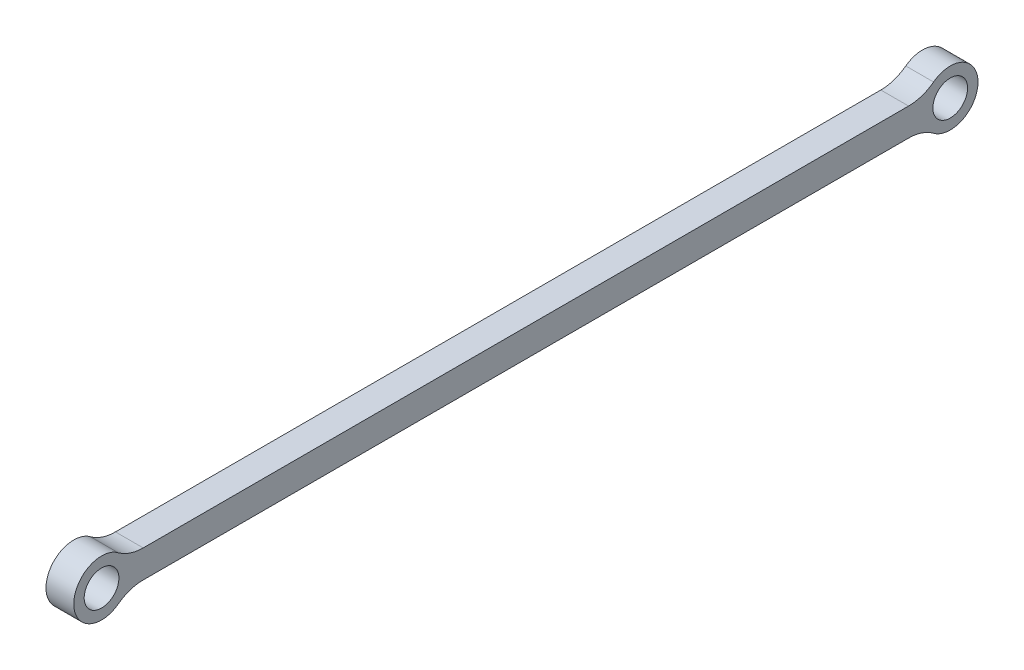
SolidWorks part; units mm, degrees
material "Thornel Mat VMA"
ref_plane "前视基准面" through (0, 0, 0) normal (0, 0, 1) x (1, 0, 0)
ref_plane "上视基准面" through (0, 0, 0) normal (0, 1, 0) x (1, 0, 0)
ref_plane "右视基准面" through (0, 0, 0) normal (1, 0, 0) x (0, 0, -1)
sketch "草图1" plane through (0, 0, 0) normal (1, 0, 0) x (0, 0, -1)
  line L0 (0, 0) -> (244.5, 0) construction
  line L1 (0, 8) -> (244.5, 8)
  line L2 (0, -8) -> (244.5, -8)
  arc A0 (0, 8) -> (0, -8) centre (0, 0) ccw
  arc A1 (244.5, -8) -> (244.5, 8) centre (244.5, 0) ccw
  circle A2 centre (244.5, 0) radius 5
  circle A3 centre (0, 0) radius 5
  point P3 (122.25, 0)
  dimension "D1" = 10
  dimension "D2" = 10
  dimension "D3" = 16
  dimension "D4" = 244.5
extrude "凸台-拉伸1" add sketch "草图1" along normal blind 8
sketch "草图2" plane through (8, 0, 0) normal (1, 0, 0) x (0, 0, -1)
  line L0 (0, 0) -> (244.5, 0) construction
  line L1 (0, -8) -> (244.5, -8) construction
  line L2 (244.5, 8) -> (0, 8) construction
  line L3 (237.5718, -4) -> (6.9282, -4)
  line L4 (237.5718, 4) -> (6.9282, 4)
  line L5 (0, -8) -> (244.5, -8)
  line L6 (244.5, 8) -> (0, 8)
  arc A0 (0, -8) -> (6.9282, -4) centre (0, 0) ccw
  arc A1 (0, 8) -> (0, -8) centre (0, 0) ccw construction
  arc A2 (244.5, 8) -> (237.5718, 4) centre (244.5, 0) ccw
  arc A3 (6.9282, 4) -> (0, 8) centre (0, 0) ccw
  arc A4 (237.5718, -4) -> (244.5, -8) centre (244.5, 0) ccw
  dimension "D1" = 8
extrude "切除-拉伸1" cut sketch "草图2" against normal through all
fillet "圆角1" radius 12 4 edges at (4, -4, -237.5718) (4, 4, -6.9282) (4, -4, -6.9282) (4, 4, -237.5718)
sketch "草图4" plane through (8, 0, 0) normal (1, 0, 0) x (0, 0, -1)
  line L0 (0, 0) -> (244.5, 0) construction
  line L1 (122.25, 0) -> (122.25, 19.2035) construction
  line L2 (12, 4) -> (232.5, 4) construction
  line L6 (121.75, 2.2) -> (109.75, 2.2)
  line L9 (121.75, 2.2) -> (121.75, -2.2)
  line L12 (121.75, -2.2) -> (109.75, -2.2)
  line L15 (109.75, 2.2) -> (109.75, -2.2)
  line L18 (121.75, 2.2) -> (109.75, -2.2) construction
  line L21 (214.75, -2.2) -> (200.75, 2.2) construction
  line L24 (121.75, -2.2) -> (109.75, 2.2) construction
  line L27 (108.75, 2.2) -> (96.75, 2.2)
  line L30 (96.75, 2.2) -> (96.75, -2.2)
  line L33 (108.75, 2.2) -> (108.75, -2.2)
  line L36 (108.75, -2.2) -> (96.75, -2.2)
  line L39 (95.75, 2.2) -> (83.75, 2.2)
  line L46 (83.75, 2.2) -> (83.75, -2.2)
  line L47 (95.75, 2.2) -> (95.75, -2.2)
  line L48 (95.75, -2.2) -> (83.75, -2.2)
  line L49 (82.75, 2.2) -> (70.75, 2.2)
  line L50 (70.75, 2.2) -> (70.75, -2.2)
  line L51 (82.75, 2.2) -> (82.75, -2.2)
  line L52 (82.75, -2.2) -> (70.75, -2.2)
  line L53 (69.75, 2.2) -> (57.75, 2.2)
  line L54 (57.75, 2.2) -> (57.75, -2.2)
  line L55 (69.75, 2.2) -> (69.75, -2.2)
  line L56 (69.75, -2.2) -> (57.75, -2.2)
  line L57 (56.75, 2.2) -> (44.75, 2.2)
  line L58 (44.75, 2.2) -> (44.75, -2.2)
  line L59 (56.75, 2.2) -> (56.75, -2.2)
  line L60 (56.75, -2.2) -> (44.75, -2.2)
  line L61 (29.75, 2.2) -> (43.75, 2.2)
  line L62 (29.75, 2.2) -> (29.75, -2.2)
  line L63 (29.75, -2.2) -> (43.75, -2.2)
  line L64 (43.75, 2.2) -> (43.75, -2.2)
  line L65 (29.75, 2.2) -> (43.75, -2.2) construction
  line L66 (29.75, -2.2) -> (43.75, 2.2) construction
  line L67 (214.75, 2.2) -> (200.75, -2.2) construction
  line L68 (122.75, -2.2) -> (134.75, 2.2) construction
  line L69 (122.75, 2.2) -> (134.75, -2.2) construction
  line L70 (200.75, 2.2) -> (200.75, -2.2)
  line L71 (214.75, -2.2) -> (200.75, -2.2)
  line L72 (214.75, 2.2) -> (214.75, -2.2)
  line L73 (214.75, 2.2) -> (200.75, 2.2)
  line L74 (187.75, -2.2) -> (199.75, -2.2)
  line L75 (187.75, 2.2) -> (187.75, -2.2)
  line L76 (199.75, 2.2) -> (199.75, -2.2)
  line L77 (187.75, 2.2) -> (199.75, 2.2)
  line L78 (174.75, -2.2) -> (186.75, -2.2)
  line L79 (174.75, 2.2) -> (174.75, -2.2)
  line L80 (186.75, 2.2) -> (186.75, -2.2)
  line L81 (174.75, 2.2) -> (186.75, 2.2)
  line L82 (161.75, -2.2) -> (173.75, -2.2)
  line L83 (161.75, 2.2) -> (161.75, -2.2)
  line L84 (173.75, 2.2) -> (173.75, -2.2)
  line L85 (161.75, 2.2) -> (173.75, 2.2)
  line L86 (148.75, -2.2) -> (160.75, -2.2)
  line L87 (148.75, 2.2) -> (148.75, -2.2)
  line L88 (160.75, 2.2) -> (160.75, -2.2)
  line L89 (148.75, 2.2) -> (160.75, 2.2)
  line L90 (135.75, -2.2) -> (147.75, -2.2)
  line L91 (135.75, 2.2) -> (135.75, -2.2)
  line L92 (147.75, 2.2) -> (147.75, -2.2)
  line L93 (135.75, 2.2) -> (147.75, 2.2)
  line L94 (134.75, 2.2) -> (134.75, -2.2)
  line L95 (122.75, -2.2) -> (134.75, -2.2)
  line L96 (122.75, 2.2) -> (122.75, -2.2)
  line L97 (122.75, 2.2) -> (134.75, 2.2)
  point P6 (115.75, 0)
  point P13 (36.75, 0)
  point P66 (207.75, 0)
  point P67 (128.75, 0)
  dimension "D2" = 1.8
  dimension "D3" = 12
  dimension "D5" = 13
  dimension "D6" = 1
  dimension "D7" = 14
  dimension "D1" = 0.5
  dimension "D4" = 6
extrude "切除-拉伸2" [suppressed] cut sketch "草图4" against normal through all
fillet "圆角2" [suppressed] radius 1.5
sketch "草图5" plane through (8, 0, 0) normal (1, 0, 0) x (0, 0, -1)
  circle A0 centre (0, 0) radius 16.9196
sketch "草图6" plane through (8, 0, 0) normal (1, 0, 0) x (0, 0, -1)
  line L0 (244.5, 0) -> (122, 0) construction
  circle A0 centre (122, 0) radius 2.5
  circle A1 centre (0, 0) radius 5 construction
  dimension "D2" = 5
  dimension "D1" = 122
move or copy body "实体-移动/复制5" bodies to move or copy 107
move or copy body "实体-移动/复制6" [suppressed] bodies to move or copy 116
move or copy body "实体-移动/复制4" [suppressed] bodies to move or copy 107
move or copy body "实体-移动/复制3" bodies to move or copy 116
move or copy body "实体-移动/复制2" [suppressed] bodies to move or copy 107
move or copy body "实体-移动/复制1" [suppressed] bodies to move or copy 111
